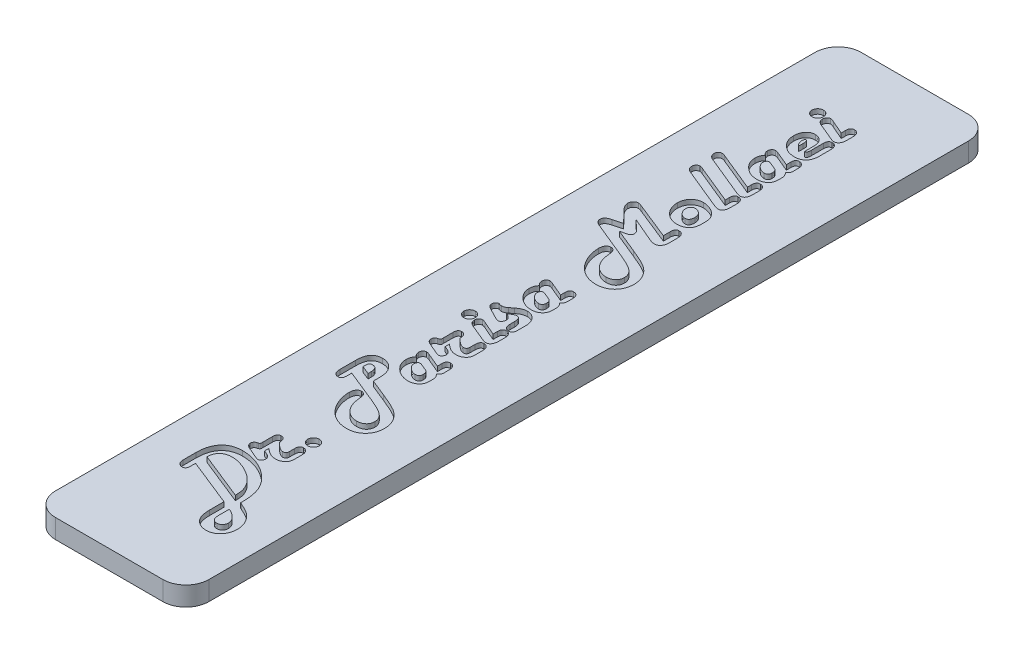
SolidWorks part; units mm, degrees
ref_plane "Front Plane" through (0, 0, 0) normal (0, 0, 1) x (1, 0, 0)
ref_plane "Top Plane" through (0, 0, 0) normal (0, 1, 0) x (1, 0, 0)
ref_plane "Right Plane" through (0, 0, 0) normal (1, 0, 0) x (0, 0, -1)
sketch "Sketch1" plane through (0, 0, 0) normal (0, 0, 1) x (1, 0, 0)
  line L0 (0, 1.5875) -> (0, -1.5875)
  line L1 (-12.7, 0) -> (12.7, 0) construction
  point P6 (0, 0)
  dimension "Width" = 25.4
  dimension "Thk" = 3.175
sketch "Sketch2" plane through (0, 0, 0) normal (1, 0, 0) x (0, 0, -1)
  line L0 (66.675, 0) -> (-66.675, 0)
  point P4 (0, 0)
  dimension "Length" = 133.35
sketch "Sketch3" plane through (0, 0, 0) normal (0, 0, 1) x (1, 0, 0)
  line L1 (12.7, 1.5875) -> (-12.7, 1.5875)
  line L2 (12.7, 1.5875) -> (12.7, -1.5875)
  line L3 (12.7, -1.5875) -> (-12.7, -1.5875)
  line L4 (-12.7, 1.5875) -> (-12.7, -1.5875)
  line L5 (12.7, 1.5875) -> (-12.7, -1.5875) construction
  line L6 (12.7, -1.5875) -> (-12.7, 1.5875) construction
  point P0 (0, 0)
extrude "Boss-Extrude1" add sketch "Sketch3" along normal up to vertex (66.675 mm away) and the other way up to vertex (66.675 mm away) up to point (0, 0, 66.675) other way up to point (0, 0, -66.675)
sketch "Sketch5" plane through (0, 1.5875, 0) normal (0, 1, 0) x (1, 0, 0)
  line L2 (9.652, -66.675) -> (-9.398, -66.675) construction
  line L3 (-12.7, -63.5025) -> (-12.7, 63.627) construction
  line L12 (12.7, -66.675) -> (12.7, 66.675)
  line L13 (12.7, 66.675) -> (-12.7, 66.675)
  line L14 (-12.7, 66.675) -> (-12.7, -66.675)
  line L15 (-12.7, -66.675) -> (12.7, -66.675)
  line L16 (12.7, -62.865) -> (12.7, 62.865)
  line L17 (8.89, 66.675) -> (-8.89, 66.675)
  line L18 (-12.7, 62.865) -> (-12.7, -62.865)
  line L19 (-8.89, -66.675) -> (8.89, -66.675)
  arc A8 (12.7, 62.865) -> (8.89, 66.675) centre (8.89, 62.865) ccw
  arc A9 (-8.89, 66.675) -> (-12.7, 62.865) centre (-8.89, 62.865) ccw
  arc A10 (12.7, -62.865) -> (8.89, -66.675) centre (8.89, -62.865) cw
  arc A11 (-8.89, -66.675) -> (-12.7, -62.865) centre (-8.89, -62.865) cw
  dimension "D2" = 3.81
  dimension "D1" = 0
extrude "Cut-Extrude2" cut sketch "Sketch5" against normal through all flip side to cut
sketch "Sketch4" plane through (0, 1.5875, 0) normal (0, 1, 0) x (1, 0, 0)
  line L0 (0, 0) -> (2.54, 0) construction
  line L1 (2.54, -66.675) -> (2.54, 66.675) construction
  line L2 (8.89, 66.675) -> (-8.89, 66.675) construction
  text T0 "Dr. Parisa Mollaei" font "Harlow Solid Italic" height in points 36
  point P8 (2.54, 0)
  dimension "D1" = 2.54
extrude "Cut-Extrude1" cut sketch "Sketch4" against normal blind 0.7937
